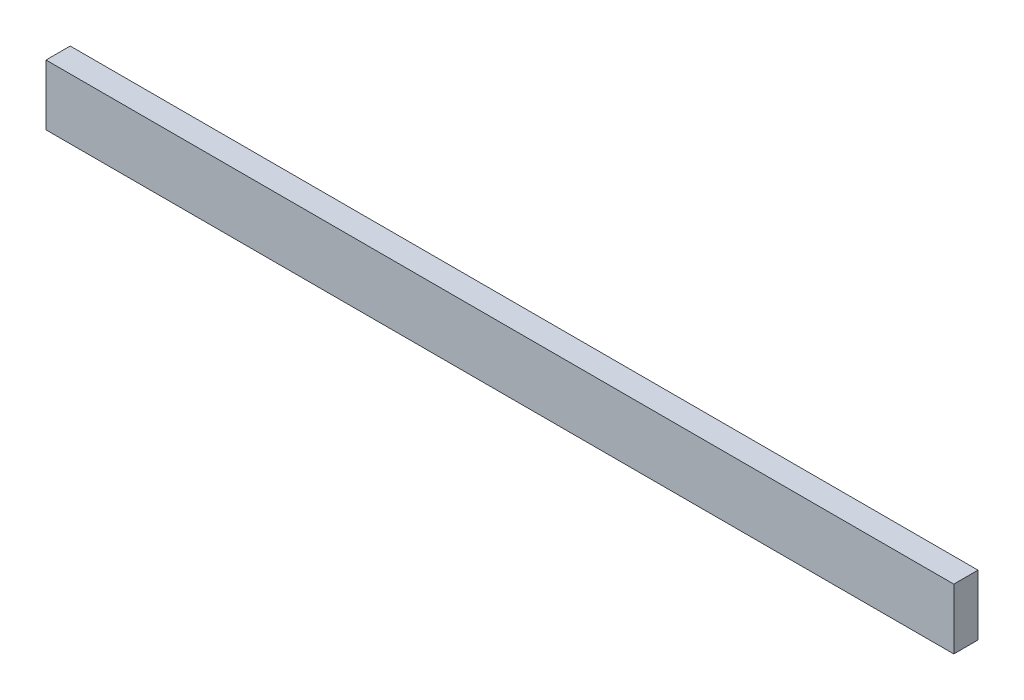
SolidWorks part; units mm, degrees
ref_plane "Alzado" through (0, 0, 0) normal (0, 0, 1) x (1, 0, 0)
ref_plane "Planta" through (0, 0, 0) normal (0, 1, 0) x (1, 0, 0)
ref_plane "Vista lateral" through (0, 0, 0) normal (1, 0, 0) x (0, 0, -1)
sketch "Croquis1" plane through (0, 0, 0) normal (0, 0, 1) x (1, 0, 0)
  line L1 (0, 0) -> (150, 0)
  line L2 (0, 0) -> (0, 10)
  line L3 (0, 10) -> (150, 10)
  line L4 (150, 0) -> (150, 10)
  dimension "D1" = 150
  dimension "D2" = 10
extrude "Saliente-Extruir1" add sketch "Croquis1" along normal blind 4
